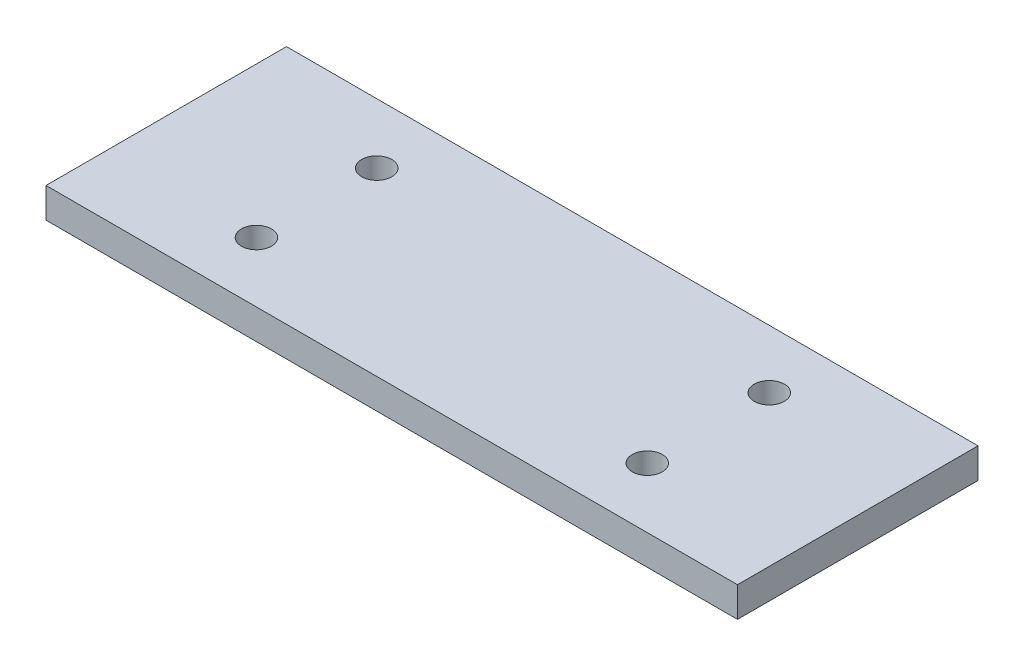
SolidWorks part; units mm, degrees
ref_plane "Front Plane" through (0, 0, 0) normal (0, 0, 1) x (1, 0, 0)
ref_plane "Top Plane" through (0, 0, 0) normal (0, 1, 0) x (1, 0, 0)
ref_plane "Right Plane" through (0, 0, 0) normal (1, 0, 0) x (0, 0, -1)
sketch "Sketch1" plane through (0, 0, 0) normal (0, 1, 0) x (1, 0, 0)
  line L1 (-57.5, 20) -> (57.5, 20)
  line L2 (-57.5, 20) -> (-57.5, -20)
  line L3 (-57.5, -20) -> (57.5, -20)
  line L4 (57.5, 20) -> (57.5, -20)
  line L5 (-57.5, 20) -> (57.5, -20) construction
  line L6 (-57.5, -20) -> (57.5, 20) construction
  point P0 (0, 0)
  dimension "D1" = 40
  dimension "D2" = 115
extrude "Boss-Extrude1" add sketch "Sketch1" along normal mid plane 5
hole_wizard "Ø5.0mm Dowel Hole1" positions "Sketch2" profile "Sketch3" hole size "Ø5.0" standard "ISO" end condition through all
sketch "Sketch2" plane through (0, 2.5, 0) normal (0, 1, 0) x (1, 0, 0)
  line L0 (57.5, 20) -> (-57.5, 20) construction
  line L1 (-57.5, 20) -> (-57.5, -20) construction
  point P0 (-32.5, 10)
  point P2 (-32.5, -10)
  point P4 (32.5, -10)
  point P6 (32.5, 10.2905)
  dimension "D1" = 10
  dimension "D2" = 65
  dimension "D3" = 25
  dimension "D4" = 20
sketch "Sketch3" plane through (-32.5, 2.5, -10) normal (1, 0, 0) x (0, 0, 1)
  line L0 (0, 0) -> (0, 5)
  line L1 (0, 5) -> (2.5, 5)
  line L2 (2.5, 5) -> (2.5, 0)
  line L5 (2.5, 0) -> (0, 0)
  line L11 (0, -6.35) -> (0, 107.95) construction
  dimension "Thru Hole Dia." = 5
  dimension "Thru Hole Depth" = 5
